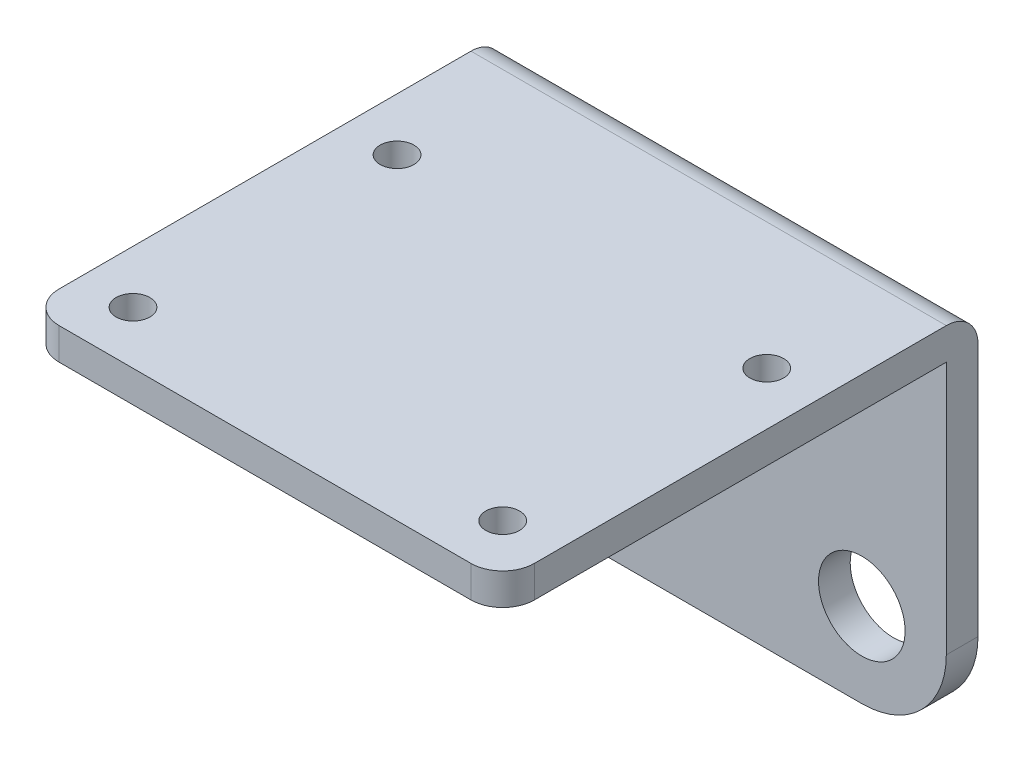
SolidWorks part; units mm, degrees
ref_plane "前视基准面" through (0, 0, 0) normal (0, 0, 1) x (1, 0, 0)
ref_plane "上视基准面" through (0, 0, 0) normal (0, 1, 0) x (1, 0, 0)
ref_plane "右视基准面" through (0, 0, 0) normal (1, 0, 0) x (0, 0, -1)
other "Configuration Table"
sketch "草图1" plane through (0, 0, 0) normal (0, 1, 0) x (1, 0, 0)
  line L1 (-22.5, 22.5) -> (22.5, 22.5)
  line L2 (-22.5, 22.5) -> (-22.5, -22.5)
  line L3 (-22.5, -22.5) -> (22.5, -22.5)
  line L4 (22.5, 22.5) -> (22.5, -22.5)
  line L5 (-22.5, 22.5) -> (22.5, -22.5) construction
  line L6 (-22.5, -22.5) -> (22.5, 22.5) construction
  circle A0 centre (-17.5, -17.5) radius 1.6
  circle A1 centre (17.5, -17.5) radius 1.6
  circle A2 centre (17.5, 7.5) radius 1.6
  circle A3 centre (-17.5, 7.5) radius 1.6
  point P0 (0, 0)
  dimension "D3" = 3.2
  dimension "D4" = 5
  dimension "D5" = 5
  dimension "D8" = 35
  dimension "D9" = 25
  dimension "D1" = 45
  dimension "D2" = 45
  dimension "D6" = 2
  dimension "D7" = 2
extrude "凸台-拉伸1" add sketch "草图1" along normal blind 3
sketch "草图2" plane through (0, 0, 0) normal (0, -1, 0) x (1, 0, 0)
  line L0 (-22.5, -22.5) -> (-22.5, 22.5) construction
  line L1 (22.5, -22.5) -> (-22.5, -22.5)
  line L2 (22.5, -22.5) -> (22.5, -19.5)
  line L3 (22.5, -19.5) -> (-22.5, -19.5)
  line L4 (-22.5, -22.5) -> (-22.5, -19.5)
  dimension "D1" = 3
extrude "凸台-拉伸2" add sketch "草图2" along normal blind 32
sketch "草图3" plane through (0, 0, -22.5) normal (0, 0, -1) x (-1, 0, 0)
  line L1 (-22.5, -32) -> (22.5, -32) construction
  line L2 (-22.5, -32) -> (-22.5, 0) construction
  line L3 (-22.5, 0) -> (22.5, 0) construction
  line L4 (22.5, -32) -> (22.5, 0) construction
  circle A0 centre (-14.5, -24) radius 4.1
  circle A1 centre (14.5, -24) radius 4.1
  dimension "D1" = 8.2
  dimension "D2" = 8
  dimension "D3" = 8
  dimension "D4" = 8.2
  dimension "D5" = 8
  dimension "D6" = 8
  dimension "D7" = 29
extrude "切除-拉伸1" cut sketch "草图3" against normal up to next
fillet "圆角1" radius 3 3 edges at (0, 3, -22.5) (22.5, 1.5, 22.5) (-22.5, 1.5, 22.5)
fillet "圆角2" radius 8 2 edges at (-22.5, -32, -21) (22.5, -32, -21)
